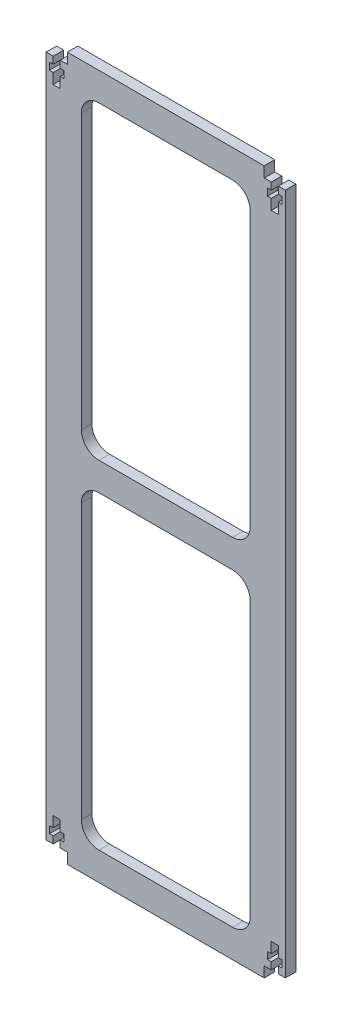
SolidWorks part; units mm, degrees
ref_plane "Front" through (0, 0, 0) normal (0, 0, 1) x (1, 0, 0)
ref_plane "Top" through (0, 0, 0) normal (0, 1, 0) x (1, 0, 0)
ref_plane "Right" through (0, 0, 0) normal (1, 0, 0) x (0, 0, -1)
sketch "草图1" plane through (0, 0, 0) normal (0, 0, 1) x (1, 0, 0)
  line L1 (0, 0) -> (68, 0)
  line L2 (0, 0) -> (0, 200)
  line L3 (0, 200) -> (68, 200)
  line L4 (68, 0) -> (68, 200)
  dimension "D1" = 200
  dimension "D2" = 68
extrude "凸台-拉伸1" add sketch "草图1" along normal blind 3
sketch "草图2" plane through (0, 0, 3) normal (0, 0, 1) x (1, 0, 0)
  line L0 (68, 0) -> (68, 200) construction
  line L1 (68, 197) -> (62, 197)
  line L2 (68, 197) -> (68, 200)
  line L3 (68, 200) -> (62, 200)
  line L4 (62, 197) -> (62, 200)
  line L5 (68, 200) -> (0, 200) construction
  line L6 (0, 200) -> (0, 0) construction
  line L7 (6, 200) -> (0, 200)
  line L8 (6, 200) -> (6, 197)
  line L9 (6, 197) -> (0, 197)
  line L10 (0, 200) -> (0, 197)
  line L12 (68, 0) -> (62, 0)
  line L13 (68, 0) -> (68, 3)
  line L14 (68, 3) -> (62, 3)
  line L15 (62, 0) -> (62, 3)
  line L16 (0, 0) -> (6, 0)
  line L17 (0, 0) -> (0, 3)
  line L18 (0, 3) -> (6, 3)
  line L19 (6, 0) -> (6, 3)
  dimension "D1" = 6
  dimension "D2" = 3
  dimension "D3" = 6
  dimension "D4" = 3
  dimension "D5" = 3
extrude "切除-拉伸1" cut sketch "草图2" against normal through all
sketch "草图3" plane through (0, 0, 3) normal (0, 0, 1) x (1, 0, 0)
  line L0 (68, 3) -> (68, 197) construction
  line L1 (58, 192) -> (10, 192)
  line L2 (58, 192) -> (58, 104)
  line L3 (58, 104) -> (10, 104)
  line L4 (10, 192) -> (10, 104)
  line L6 (62, 200) -> (6, 200) construction
  line L7 (58, 96) -> (10, 96)
  line L8 (58, 96) -> (58, 8)
  line L9 (58, 8) -> (10, 8)
  line L10 (10, 96) -> (10, 8)
  line L11 (6, 0) -> (62, 0) construction
  dimension "D1" = 88
  dimension "D2" = 48
  dimension "D3" = 10
  dimension "D4" = 88
  dimension "D5" = 48
  dimension "D6" = 10
  dimension "D7" = 8
  dimension "D8" = 8
extrude "切除-拉伸2" cut sketch "草图3" against normal through all
fillet "圆角1" radius 5 8 edges at (58, 8, 1.5) (10, 8, 1.5) (10, 96, 1.5) (58, 96, 1.5) (58, 104, 1.5) (10, 104, 1.5) (10, 192, 1.5) (58, 192, 1.5)
sketch "草图4" plane through (0, 0, 3) normal (0, 0, 1) x (1, 0, 0)
  line L0 (6, 3) -> (0, 3) construction
  line L1 (2, 3) -> (4, 3)
  line L2 (2, 3) -> (2, 5)
  line L3 (2, 10) -> (4, 10)
  line L4 (4, 3) -> (4, 5)
  line L5 (0, 197) -> (6, 197) construction
  line L6 (0.95, 5) -> (2, 5)
  line L7 (0.95, 5) -> (0.95, 7)
  line L8 (0.95, 7) -> (2, 7)
  line L9 (5.05, 5) -> (5.05, 7)
  line L10 (2, 7) -> (2, 10)
  line L11 (4, 5) -> (5.05, 5)
  line L12 (4, 7) -> (5.05, 7)
  line L13 (4, 7) -> (4, 10)
  point P10 (3, 3)
  point P13 (3, 197)
  dimension "D1" = 2
  dimension "D2" = 4.1
  dimension "D3" = 1.05
  dimension "D4" = 2
  dimension "D5" = 2
  dimension "D6" = 7
  dimension "D7" = 0
extrude "切除-拉伸3" cut sketch "草图4" against normal through all
pattern_linear "阵列(线性)1" count 2 spacing 62 along (1, 0, 0) of "切除-拉伸3"
ref_plane "基准面1" through (0, 100, 0) normal (0, -1, 0) x (-1, 0, 0)
mirror "镜向1" about plane through (0, 100, 0) normal (0, -1, 0) of "阵列(线性)1", "切除-拉伸3"
